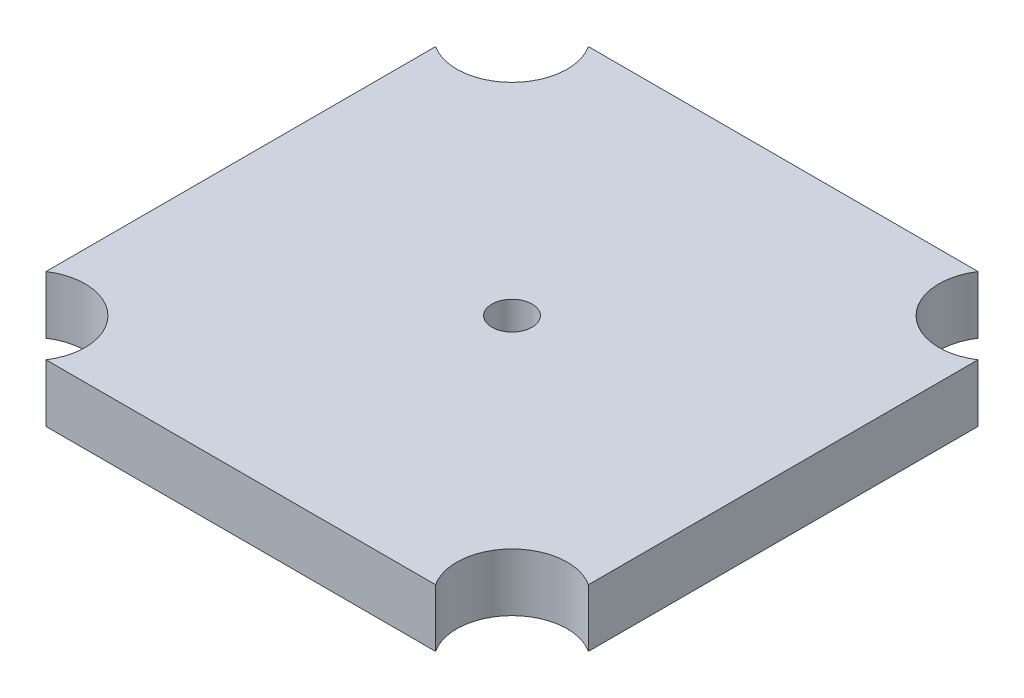
SolidWorks part; units mm, degrees
material "Pine"
ref_plane "Front Plane" through (0, 0, 0) normal (0, 0, 1) x (1, 0, 0)
ref_plane "Top Plane" through (0, 0, 0) normal (0, 1, 0) x (1, 0, 0)
ref_plane "Right Plane" through (0, 0, 0) normal (1, 0, 0) x (0, 0, -1)
sketch "Sketch1" plane through (0, 0, 0) normal (0, 1, 0) x (1, 0, 0)
  line L1 (-85.725, -85.725) -> (85.725, -85.725)
  line L2 (-85.725, -85.725) -> (-85.725, 85.725)
  line L3 (-85.725, 85.725) -> (85.725, 85.725)
  line L4 (85.725, -85.725) -> (85.725, 85.725)
  line L5 (-85.725, -85.725) -> (85.725, 85.725) construction
  line L6 (-85.725, 85.725) -> (85.725, -85.725) construction
  point P0 (0, 0)
  dimension "D1" = 171.45
extrude "Boss-Extrude1" add sketch "Sketch1" along normal blind 18.2562
sketch "Sketch2" plane through (0, 18.2562, 0) normal (0, 1, 0) x (1, 0, 0)
  line L0 (-76.2, -76.2) -> (-76.2, 76.2) construction
  line L1 (-76.2, 76.2) -> (76.2, 76.2) construction
  line L2 (76.2, 76.2) -> (76.2, -76.2) construction
  line L3 (76.2, -76.2) -> (-76.2, -76.2) construction
  line L4 (-76.2, 76.2) -> (76.2, -76.2) construction
  line L5 (-76.2, -76.2) -> (76.2, 76.2) construction
  circle A0 centre (-76.2, 76.2) radius 17.4625
  circle A1 centre (76.2, 76.2) radius 17.4625
  circle A2 centre (76.2, -76.2) radius 17.4625
  circle A3 centre (-76.2, -76.2) radius 17.4625
  dimension "D2" = 34.925
  dimension "D1" = 152.4
extrude "Cut-Extrude1" cut sketch "Sketch2" against normal through all
hole_wizard "1/2 (0.5) Diameter Hole1" positions "Sketch3" profile "Sketch4" hole size "1/2" standard "ANSI Inch" end condition through all
sketch "Sketch3" plane through (0, 18.2562, 0) normal (0, 1, 0) x (1, 0, 0)
  point P0 (0, 0)
sketch "Sketch4" plane through (0, 18.2562, 0) normal (1, 0, 0) x (0, 0, 1)
  line L0 (0, 0) -> (0, 18.2562)
  line L1 (0, 18.2562) -> (6.35, 18.2562)
  line L2 (6.35, 18.2562) -> (6.35, 0)
  line L5 (6.35, 0) -> (0, 0)
  line L11 (0, -6.35) -> (0, 107.95) construction
  dimension "Thru Hole Dia." = 12.7
  dimension "Thru Hole Depth" = 18.2562
